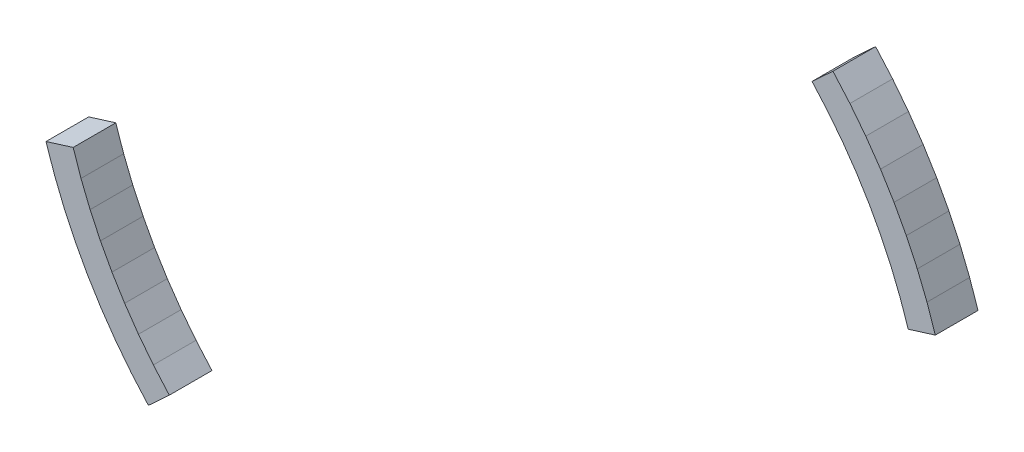
SolidWorks part; units mm, degrees
ref_plane "Front Plane" through (0, 0, 0) normal (0, 0, 1) x (1, 0, 0)
ref_plane "Top Plane" through (0, 0, 0) normal (0, 1, 0) x (1, 0, 0)
ref_plane "Right Plane" through (0, 0, 0) normal (1, 0, 0) x (0, 0, -1)
sketch "草圖1" plane through (0, 0, 0) normal (0, 0, 1) x (1, 0, 0)
  line L0 (62.5368, 19.4781) -> (61.362, 22.9118)
  line L1 (61.362, 22.9118) -> (59.9989, 26.2752)
  line L2 (59.9989, 26.2752) -> (58.4515, 29.558)
  line L3 (58.4515, 29.558) -> (56.7247, 32.75)
  line L4 (56.7247, 32.75) -> (54.8237, 35.8415)
  line L5 (54.8237, 35.8415) -> (52.7544, 38.8229)
  line L6 (52.7544, 38.8229) -> (50.5232, 41.6852)
  line L7 (50.5232, 41.6852) -> (48.1369, 44.4195)
  line L8 (48.1369, 44.4195) -> (45.1972, 41.7068)
  line L9 (45.1972, 41.7068) -> (47.4378, 39.1395)
  line L10 (47.4378, 39.1395) -> (49.5328, 36.452)
  line L11 (49.5328, 36.452) -> (51.4757, 33.6527)
  line L12 (51.4757, 33.6527) -> (53.2606, 30.75)
  line L13 (53.2606, 30.75) -> (54.8819, 27.7529)
  line L14 (54.8819, 27.7529) -> (56.3348, 24.6706)
  line L15 (56.3348, 24.6706) -> (57.6147, 21.5126)
  line L16 (57.6147, 21.5126) -> (58.7178, 18.2886)
  line L17 (58.7178, 18.2886) -> (62.5368, 19.4781)
  line L18 (-62.5368, -19.4781) -> (-61.362, -22.9118)
  line L19 (-61.362, -22.9118) -> (-59.9989, -26.2752)
  line L20 (-59.9989, -26.2752) -> (-58.4515, -29.558)
  line L21 (-58.4515, -29.558) -> (-56.7247, -32.75)
  line L22 (-56.7247, -32.75) -> (-54.8237, -35.8415)
  line L23 (-54.8237, -35.8415) -> (-52.7544, -38.8229)
  line L24 (-52.7544, -38.8229) -> (-50.5232, -41.6852)
  line L25 (-50.5232, -41.6852) -> (-48.1369, -44.4195)
  line L26 (-48.1369, -44.4195) -> (-45.1972, -41.7068)
  line L27 (-45.1972, -41.7068) -> (-47.4378, -39.1395)
  line L28 (-47.4378, -39.1395) -> (-49.5328, -36.452)
  line L29 (-49.5328, -36.452) -> (-51.4757, -33.6527)
  line L30 (-51.4757, -33.6527) -> (-53.2606, -30.75)
  line L31 (-53.2606, -30.75) -> (-54.8819, -27.7529)
  line L32 (-54.8819, -27.7529) -> (-56.3348, -24.6706)
  line L33 (-56.3348, -24.6706) -> (-57.6147, -21.5126)
  line L34 (-57.6147, -21.5126) -> (-58.7178, -18.2886)
  line L35 (-58.7178, -18.2886) -> (-62.5368, -19.4781)
extrude "填料-伸長1" add sketch "草圖1" along normal blind 6 from offset 5.5
